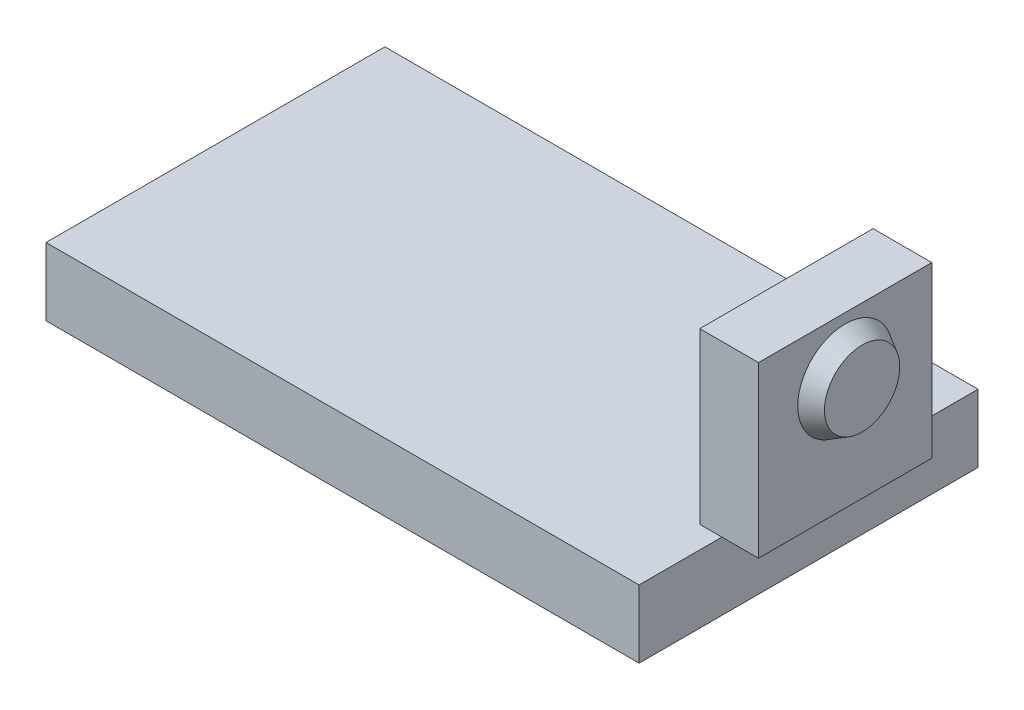
SolidWorks part; units mm, degrees
material "PVB"
ref_plane "Front Plane" through (0, 0, 0) normal (0, 0, 1) x (1, 0, 0)
ref_plane "Top Plane" through (0, 0, 0) normal (0, 1, 0) x (1, 0, 0)
ref_plane "Right Plane" through (0, 0, 0) normal (1, 0, 0) x (0, 0, -1)
sketch "Sketch1" plane through (0, 0, 0) normal (0, 1, 0) x (1, 0, 0)
  line L1 (-17.5, 10) -> (17.5, 10)
  line L2 (-17.5, 10) -> (-17.5, -10)
  line L3 (-17.5, -10) -> (17.5, -10)
  line L4 (17.5, 10) -> (17.5, -10)
  line L5 (-17.5, 10) -> (17.5, -10) construction
  line L6 (-17.5, -10) -> (17.5, 10) construction
  point P0 (0, 0)
  dimension "D1" = 20
  dimension "D2" = 35
extrude "Boss-Extrude1" add sketch "Sketch1" along normal blind 4
sketch "Sketch2" plane through (0, 4, 0) normal (0, 1, 0) x (1, 0, 0)
  line L1 (16.1941, 5.113) -> (19.6609, 5.113)
  line L2 (16.1941, 5.113) -> (16.1941, -5.113)
  line L3 (16.1941, -5.113) -> (19.6609, -5.113)
  line L4 (19.6609, 5.113) -> (19.6609, -5.113)
  line L5 (16.1941, 5.113) -> (19.6609, -5.113) construction
  line L6 (16.1941, -5.113) -> (19.6609, 5.113) construction
  point P0 (17.9275, 0)
  point P5 (0, 0)
extrude "Boss-Extrude2" add sketch "Sketch2" along normal blind 10
sketch "Sketch3" plane through (19.6609, 0, 0) normal (1, 0, 0) x (0, 0, -1)
  circle A0 centre (0, 10.6175) radius 2.8001
  point P2 (0.587, 9.5501)
  point P3 (0, 0)
  point P4 (0, 8.6817)
  point P5 (0, 10.6175)
extrude "Boss-Extrude3" add sketch "Sketch3" along normal blind 1 draft 30
